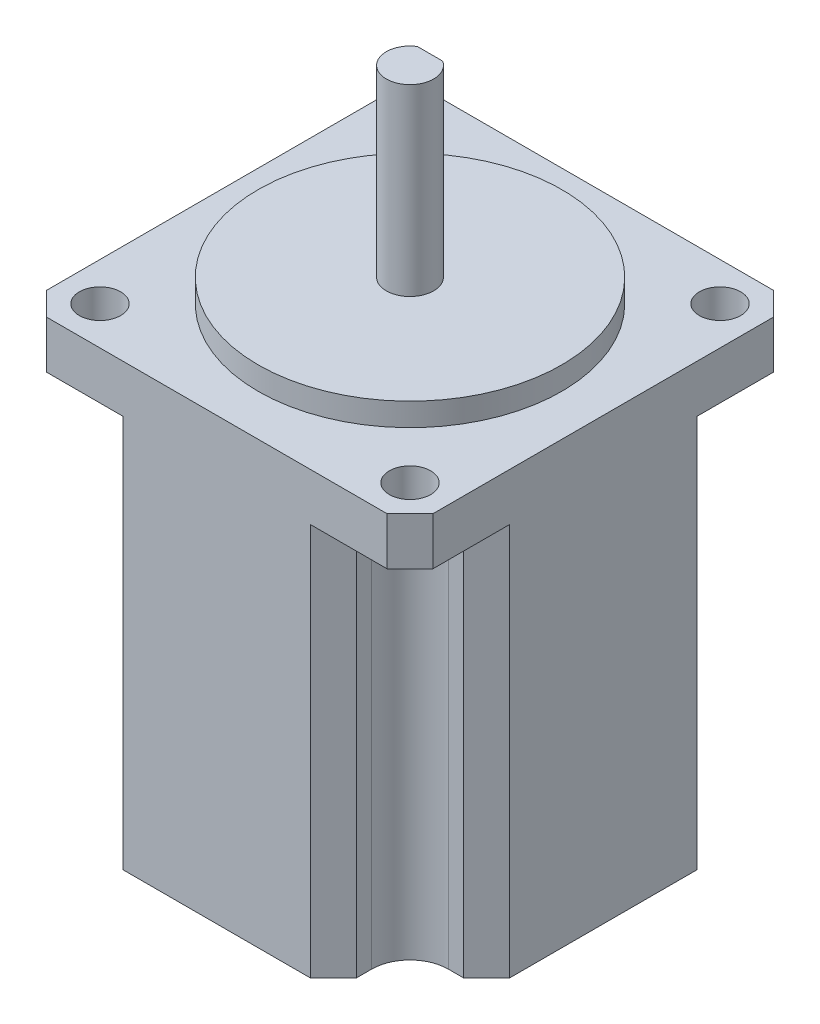
SolidWorks part; units mm, degrees
ref_plane "Alzado" through (0, 0, 0) normal (0, 0, 1) x (1, 0, 0)
ref_plane "Planta" through (0, 0, 0) normal (0, 1, 0) x (1, 0, 0)
ref_plane "Vista lateral" through (0, 0, 0) normal (1, 0, 0) x (0, 0, -1)
sketch "Croquis1" plane through (0, 0, 0) normal (0, 1, 0) x (1, 0, 0)
  line L1 (21.07, 21.07) -> (-21.07, 21.07)
  line L2 (21.07, 21.07) -> (21.07, -21.07)
  line L3 (21.07, -21.07) -> (-21.07, -21.07)
  line L4 (-21.07, 21.07) -> (-21.07, -21.07)
  line L5 (21.07, 21.07) -> (-21.07, -21.07) construction
  line L6 (21.07, -21.07) -> (-21.07, 21.07) construction
  point P0 (0, 0)
  dimension "D1" = 42.14
extrude "Saliente-Extruir1" add sketch "Croquis1" along normal blind 48
ref_plane "Plano1" through (0, 42.8, 0) normal (0, 1, 0) x (1, 0, 0)
sketch "Croquis2" plane through (0, 42.8, 0) normal (0, 1, 0) x (1, 0, 0)
  line L0 (-21.07, 12.72) -> (-16.895, 12.72)
  line L3 (-21.07, 21.07) -> (-21.07, -21.07) construction
  line L4 (-12.72, 16.895) -> (-12.72, 21.07)
  line L6 (21.07, 21.07) -> (-21.07, 21.07) construction
  line L7 (-21.07, 12.72) -> (-21.07, 21.07)
  line L8 (-21.07, 21.07) -> (-12.72, 21.07)
  arc A0 (-16.895, 12.72) -> (-12.72, 16.895) centre (-16.895, 16.895) ccw
  point P11 (-21.07, 16.895)
  dimension "D1" = 8.35
extrude "Cortar-Extruir1" cut sketch "Croquis2" against normal through all
mirror "Simetría3" about plane through (0, 0, 0) normal (1, 0, 0) of "Cortar-Extruir1" second plane through (0, 0, 0) second plane normal (0, 0, 1)
chamfer "Chaflán1" distance 2.5 angle 45 8 edges at (-21.07, 21.4, -12.72) (-12.72, 21.4, -21.07) (-21.07, 21.4, 12.72) (-12.72, 21.4, 21.07) (21.07, 21.4, -12.72) (12.72, 21.4, -21.07) (21.07, 21.4, 12.72) (12.72, 21.4, 21.07)
sketch "Croquis3" plane through (0, 42.8, 0) normal (0, -1, 0) x (1, 0, 0)
  circle A1 centre (16.895, -16.895) radius 2.25
  arc A2 (16.895, -12.72) -> (12.72, -16.895) centre (16.895, -16.895) ccw construction
  dimension "D1" = 4.5
extrude "Cortar-Extruir2" cut sketch "Croquis3" against normal through all
mirror "Simetría4" about plane through (0, 0, 0) normal (1, 0, 0) of "Cortar-Extruir2" second plane through (0, 0, 0) second plane normal (0, 0, 1)
sketch "Croquis4" plane through (0, 48, 0) normal (0, 1, 0) x (1, 0, 0)
  circle A0 centre (0, 0) radius 16.55
  dimension "D1" = 33.1
extrude "Saliente-Extruir2" add sketch "Croquis4" along normal blind 2.5
sketch "Croquis6" plane through (0, 50.5, 0) normal (0, 1, 0) x (1, 0, 0)
  circle A0 centre (0, 0) radius 2.58
  dimension "D1" = 5.16
extrude "Saliente-Extruir4" add sketch "Croquis6" along normal blind 2 contours A0
sketch "Croquis7" plane through (0, 52.5, 0) normal (0, 1, 0) x (1, 0, 0)
  line L1 (-1.3799, 2.18) -> (1.3799, 2.18)
  line L2 (0, 2.18) -> (0, -2.58) construction
  arc A1 (-1.3799, 2.18) -> (1.3799, 2.18) centre (0, 0) ccw
  circle A3 centre (0, 0) radius 2.58 construction
  dimension "D1" = 4.76
extrude "Saliente-Extruir5" add sketch "Croquis7" along normal blind 18
sketch "Croquis5" plane through (0, 50.5, 0) normal (0, 1, 0) x (1, 0, 0)
  line L0 (-1.3799, 2.18) -> (1.3799, 2.18)
  line L1 (0, 5.6832) -> (0, -2.58) construction
  arc A0 (-1.3799, 2.18) -> (1.3799, 2.18) centre (0, 0) ccw
  dimension "D1" = 5.16
  dimension "D2" = 4.76
extrude "Saliente-Extruir3" add sketch "Croquis5" along normal blind 20
chamfer "Chaflán2" distance 2.5 angle 45 4 edges at (-21.07, 45.4, 21.07) (-21.07, 45.4, -21.07) (21.07, 45.4, -21.07) (21.07, 45.4, 21.07)
